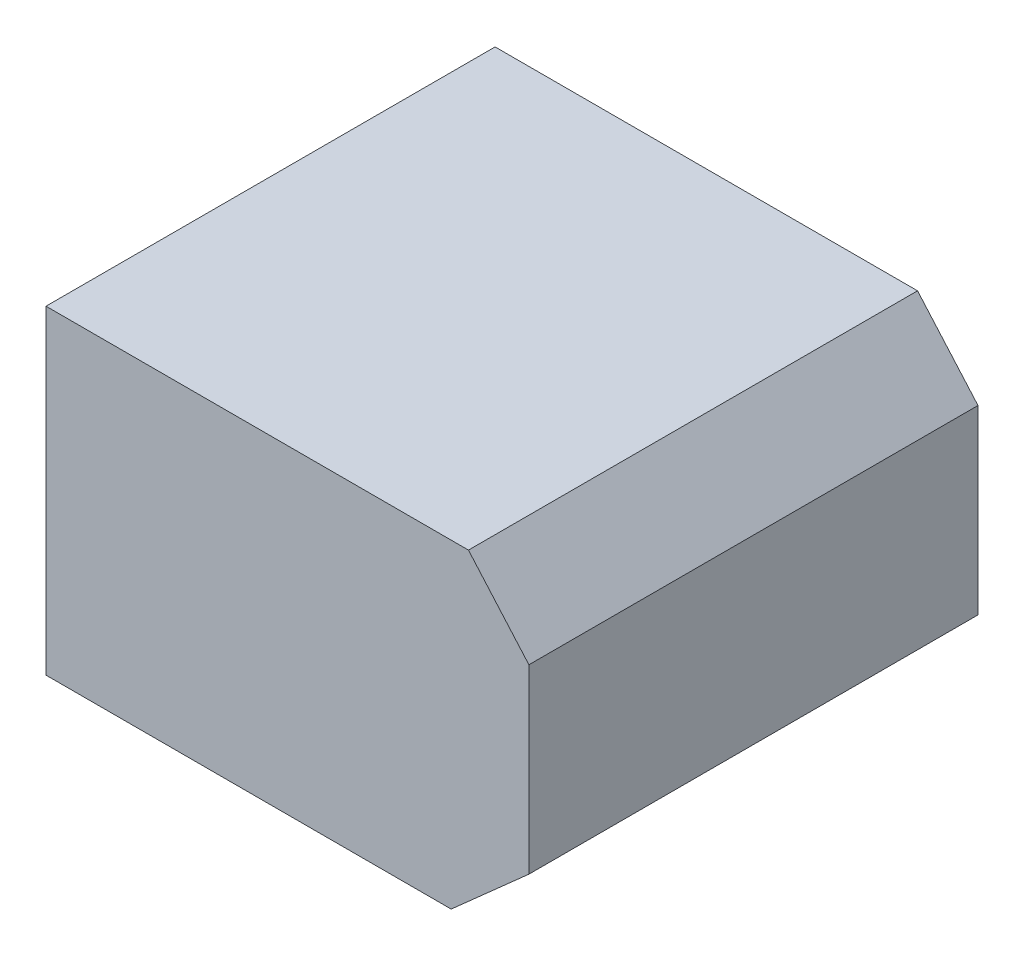
SolidWorks part; units mm, degrees
ref_plane "前视基准面" through (0, 0, 0) normal (0, 0, 1) x (1, 0, 0)
ref_plane "上视基准面" through (0, 0, 0) normal (0, 1, 0) x (1, 0, 0)
ref_plane "右视基准面" through (0, 0, 0) normal (1, 0, 0) x (0, 0, -1)
other "Configuration Table"
sketch "草图1" plane through (0, 0, 0) normal (0, 0, 1) x (1, 0, 0)
  line L0 (-0.9152, 0) -> (48, 0)
  line L1 (48, 0) -> (55, -8)
  line L2 (55, -8) -> (55, -29)
  line L3 (55, -29) -> (46, -37)
  line L4 (46, -37) -> (-0.9152, -37)
  line L5 (-0.9152, -37) -> (-0.9152, 0)
  dimension "x0" = 0.9152
  dimension "x1" = 48
  dimension "x2" = 55
  dimension "x4" = 46
  dimension "y2" = 8
  dimension "y3" = 29
  dimension "y4" = 37
extrude "Closing_lip_profile" add sketch "草图1" along normal blind 52
shell "抽壳1" thickness 5
